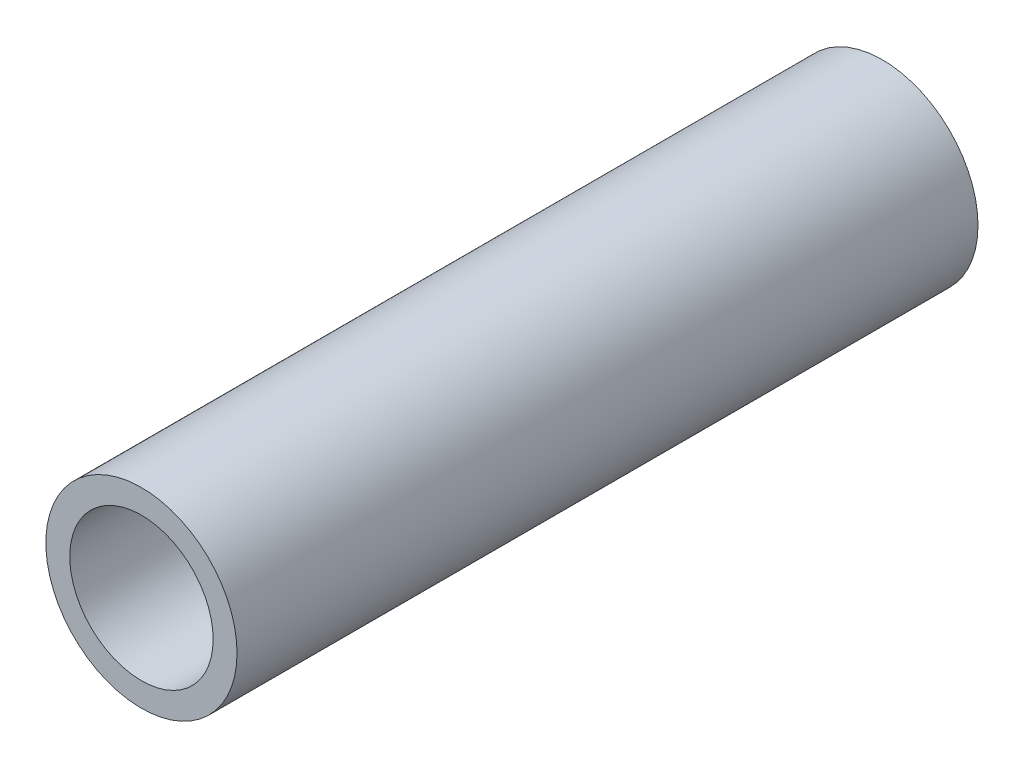
SolidWorks part; units mm, degrees
ref_plane "Front Plane" through (0, 0, 0) normal (0, 0, 1) x (1, 0, 0)
ref_plane "Top Plane" through (0, 0, 0) normal (0, 1, 0) x (1, 0, 0)
ref_plane "Right Plane" through (0, 0, 0) normal (1, 0, 0) x (0, 0, -1)
sketch "Sketch1" plane through (0, 0, 0) normal (0, 0, 1) x (1, 0, 0)
  circle A0 centre (0, 0) radius 6
  circle A1 centre (0, 0) radius 8
  dimension "D1" = 12
  dimension "D2" = 2
extrude "Boss-Extrude1" add sketch "Sketch1" along normal blind 62
